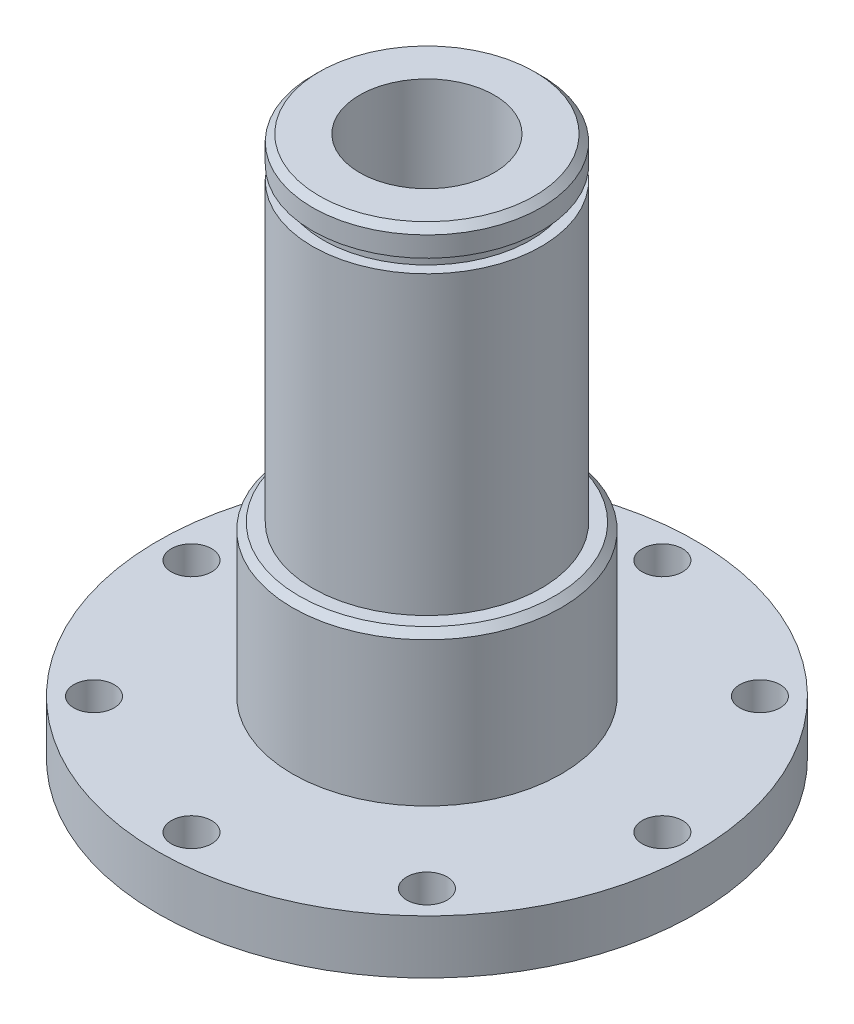
SolidWorks part; units mm, degrees
material "6061 合金"
ref_plane "前视基准面" through (0, 0, 0) normal (0, 0, 1) x (1, 0, 0)
ref_plane "上视基准面" through (0, 0, 0) normal (0, 1, 0) x (1, 0, 0)
ref_plane "右视基准面" through (0, 0, 0) normal (1, 0, 0) x (0, 0, -1)
sketch "草图1" plane through (0, 0, 0) normal (0, 1, 0) x (1, 0, 0)
  circle A0 centre (0, 0) radius 20
  dimension "D1" = 40
extrude "凸台-拉伸1" add sketch "草图1" along normal blind 4
sketch "草图2" plane through (0, 4, 0) normal (0, 1, 0) x (1, 0, 0)
  circle A0 centre (0, 0) radius 10
  dimension "D1" = 20
extrude "凸台-拉伸2" add sketch "草图2" along normal blind 11.2
sketch "草图3" plane through (0, 4, 0) normal (0, 1, 0) x (1, 0, 0)
  circle A0 centre (0, 0) radius 17.5 construction
  circle A1 centre (0, 17.5) radius 1.5
  circle A2 centre (12.3744, 12.3744) radius 1.5
  circle A3 centre (17.5, 0) radius 1.5
  circle A4 centre (12.3744, -12.3744) radius 1.5
  circle A5 centre (0, -17.5) radius 1.5
  circle A6 centre (-12.3744, -12.3744) radius 1.5
  circle A7 centre (-17.5, 0) radius 1.5
  circle A8 centre (-12.3744, 12.3744) radius 1.5
  point P21 (0, 0)
  dimension "D1" = 35
  dimension "D2" = 3
extrude "切除-拉伸1" cut sketch "草图3" against normal through all
sketch "草图4" plane through (0, 15.2, 0) normal (0, 1, 0) x (1, 0, 0)
  circle A0 centre (0, 0) radius 8.5
  dimension "D1" = 17
extrude "凸台-拉伸3" add sketch "草图4" along normal blind 25
sketch "草图5" plane through (0, 40.2, 0) normal (0, 1, 0) x (1, 0, 0)
  circle A0 centre (0, 0) radius 5
  dimension "D1" = 10
extrude "切除-拉伸2" cut sketch "草图5" against normal through all
sketch "草图6" plane through (0, 0, 0) normal (0, 0, 1) x (1, 0, 0)
  line L0 (0, 40.2) -> (0, 0) construction
  line L1 (5, 40.2) -> (-5, 40.2) construction
  line L2 (8.5, 15.2) -> (8.5, 40.2) construction
  line L3 (8.5, 38.2) -> (7.7, 38.2)
  line L4 (8.5, 38.2) -> (8.5, 37.2)
  line L5 (8.5, 37.2) -> (7.7, 37.2)
  line L6 (7.7, 38.2) -> (7.7, 37.2)
  line L7 (8.5, 40.2) -> (-8.5, 40.2) construction
  dimension "D1" = 1
  dimension "D2" = 3
  dimension "D3" = 0.8
revolve "切除-旋转1" cut sketch "草图6" angle 360 about L0
chamfer "倒角1" distance 0.5 angle 45 2 edges at (0, 15.2, 10) (0, 40.2, 8.5)
